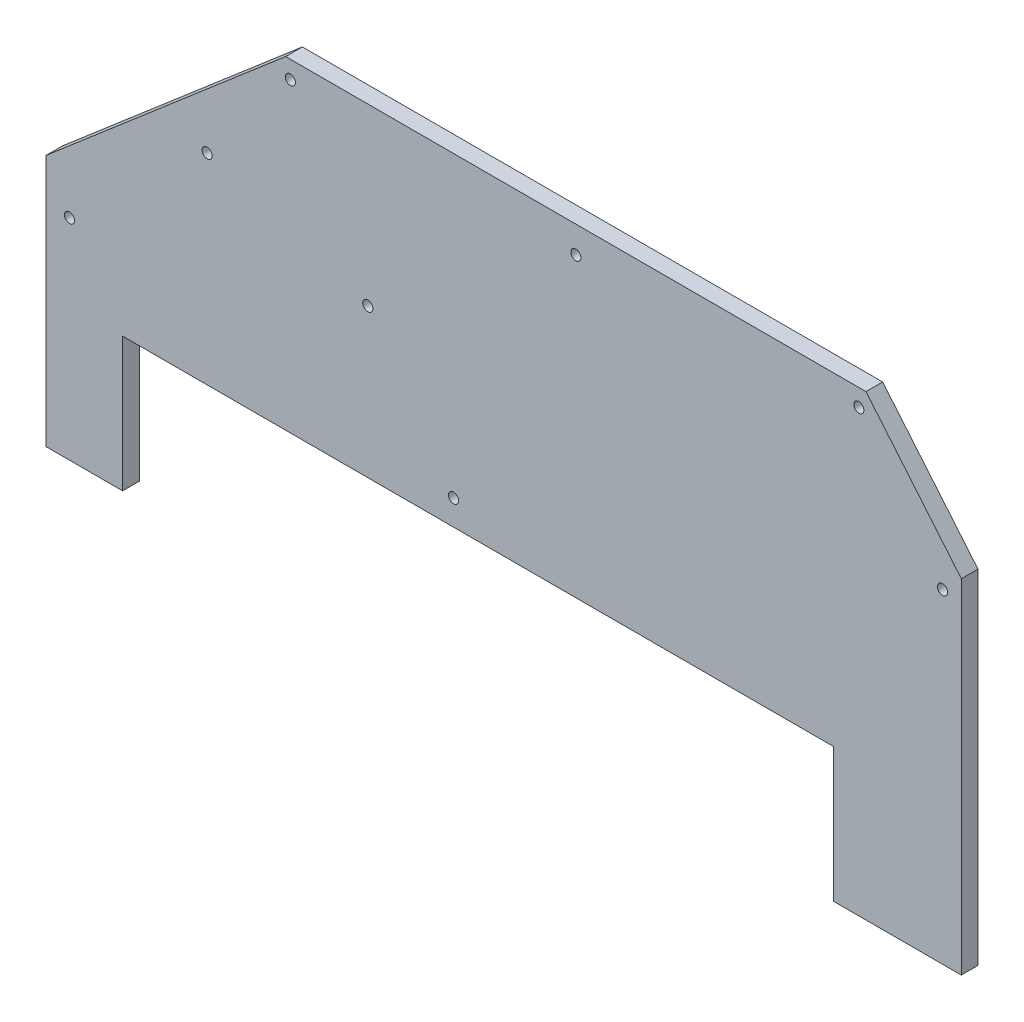
SolidWorks part; units mm, degrees
ref_plane "Front Plane" through (0, 0, 0) normal (0, 0, 1) x (1, 0, 0)
ref_plane "Top Plane" through (0, 0, 0) normal (0, 1, 0) x (1, 0, 0)
ref_plane "Right Plane" through (0, 0, 0) normal (1, 0, 0) x (0, 0, -1)
sketch "Sketch1" plane through (0, 0, 0) normal (0, 0, 1) x (1, 0, 0)
  line L0 (-558.565, 76.762) -> (-458.235, 76.762)
  line L1 (-627.78, -12.5) -> (-558.565, -12.5)
  line L2 (-627.78, -12.5) -> (-627.78, 139.9)
  line L4 (-558.565, -12.5) -> (-558.565, 76.762)
  line L6 (0, -12.5) -> (0, 216.1)
  line L8 (-458.235, -12.5) -> (-458.235, 76.762) construction
  line L9 (-449.98, 292.3) -> (-627.78, 139.9)
  line L10 (0, 216.1) -> (-63.5, 292.3)
  line L11 (-63.5, 292.3) -> (-449.98, 292.3)
  line L12 (0, 1140.6125) -> (0, 23.6125) construction
  line L13 (-449.98, 292.3) -> (-449.98, 188.3086) construction
  line L14 (-556.025, -7.42) -> (-556.025, 70.92) construction
  line L15 (-460.775, -7.42) -> (-460.775, 70.92) construction
  line L16 (-465.855, 76) -> (-550.945, 76) construction
  line L17 (-133.2337, 76) -> (-92.5937, 76) construction
  line L19 (-140.8537, -12.5) -> (-140.8537, 76.762) construction
  line L20 (-140.8537, 76.762) -> (-84.9737, 76.762)
  line L21 (-84.9737, -12.5) -> (-84.9737, 76.762)
  line L22 (-138.3137, -7.42) -> (-138.3137, 70.92) construction
  line L23 (-87.5137, 70.92) -> (-87.5137, -7.42) construction
  line L24 (0, -12.5) -> (-84.9737, -12.5)
  line L25 (-458.235, -12.5) -> (-140.8537, -12.5) construction
  line L26 (-15, 203.6) -> (-10, 203.6) construction
  line L27 (-15, 1140.6125) -> (-15, 23.6125) construction
  line L28 (-10, 23.6125) -> (-10, 1140.6125) construction
  line L29 (2.9156, 206.9655) -> (2.9156, 200.2345) construction
  line L30 (17.78, 206.9655) -> (0, 206.9655) construction
  line L31 (0, 200.2345) -> (17.78, 200.2345) construction
  line L32 (2.9156, 200.2345) -> (2.9156, 203.6) construction
  line L33 (2.9156, 203.6) -> (-12.5, 203.6) construction
  line L34 (-610, -12.5) -> (0, -12.5) construction
  line L35 (-458.235, 76.762) -> (-140.8537, 76.762)
  circle A0 centre (-12.5, 203.6) radius 3.3782
  dimension "D12" = 6.7564
  dimension "D1" = 90
  dimension "D2" = 228.6
  dimension "D3" = 304.8
  dimension "D4" = 2.54
  dimension "D5" = 2.54
  dimension "D6" = 0.762
  dimension "D7" = 177.8
  dimension "D8" = 63.5
  dimension "D9" = 0.762
  dimension "D10" = 2.54
  dimension "D11" = 2.54
extrude "Boss-Extrude1" add sketch "Sketch1" along normal blind 11.1125
extrude "Cut-Extrude1" cut sketch "Sketch2" against normal through all
sketch "Sketch2" plane through (-305, 23.6125, -5.08) normal (0, 0, -1) x (-1, 0, 0)
  line L3 (286.0006, 108.8288) -> (291.9061, 98.6002) construction
  circle A0 centre (288.9534, 103.7145) radius 3.3655
extrude "Cut-Extrude2" cut sketch "Sketch3" against normal through all
sketch "Sketch3" plane through (-305, 23.6125, -1.905) normal (0, 0, -1) x (-1, 0, 0)
  line L0 (143.1008, 263.6075) -> (140.5917, 250.2021) construction
  circle A0 centre (141.8463, 256.9048) radius 3.3655
extrude "Cut-Extrude3" cut sketch "Sketch4" against normal through all
sketch "Sketch4" plane through (-305, 23.6125, -1.905) normal (0, 0, -1) x (-1, 0, 0)
  line L1 (-48.26, 256.813) -> (-48.26, 245.002) construction
  circle A0 centre (-48.26, 250.9075) radius 3.3655
extrude "Cut-Extrude4" cut sketch "Sketch5" against normal through all
sketch "Sketch5" plane through (-305, 23.6125, -1.905) normal (0, 0, -1) x (-1, 0, 0)
  line L1 (-231.2242, 259.2462) -> (-242.3091, 255.169) construction
  circle A0 centre (-236.7667, 257.2076) radius 3.3655
extrude "Cut-Extrude5" cut sketch "Sketch6" against normal through all both and the other way through all
sketch "Sketch6" plane through (-305, 23.6125, 18.7325) normal (0, 0, 1) x (1, 0, 0)
  circle A0 centre (-197.2621, 186.927) radius 3.3782
  circle A2 centre (-33.2097, 70.0054) radius 3.3782
  circle A3 centre (-90.297, 152.235) radius 3.3782
sketch "Sketch7" plane through (0, 0, 11.1125) normal (0, 0, 1) x (1, 0, 0)
  line L0 (0, -12.5) -> (-609.6, -12.5) construction
  line L2 (-627.78, 139.9) -> (-627.78, -12.5) construction
  line L3 (-609.6, -12.5) -> (-627.78, -12.5)
  line L4 (-609.6, -12.5) -> (-609.6, 155.4829)
  line L5 (-609.6, 155.4829) -> (-627.78, 155.4829)
  line L6 (-627.78, -12.5) -> (-627.78, 155.4829)
  line L7 (-449.98, 292.3) -> (-627.78, 139.9) construction
  dimension "D1" = 609.6
extrude "Cut-Extrude6" cut sketch "Sketch7" against normal through all contours L4 L3 L6 L5
